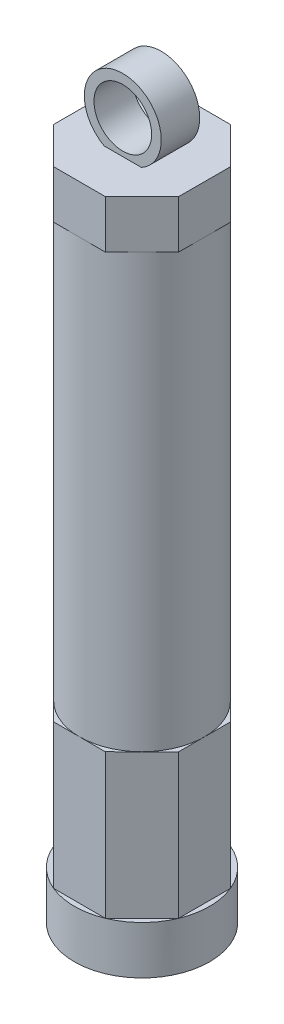
SolidWorks part; units mm, degrees
ref_plane "Front Plane" through (0, 0, 0) normal (0, 0, 1) x (1, 0, 0)
ref_plane "Top Plane" through (0, 0, 0) normal (0, 1, 0) x (1, 0, 0)
ref_plane "Right Plane" through (0, 0, 0) normal (1, 0, 0) x (0, 0, -1)
sketch "Sketch1" plane through (0, 0, 0) normal (0, 1, 0) x (1, 0, 0)
  circle A0 centre (0, 0) radius 6.5
  dimension "D1" = 13
extrude "Boss-Extrude1" add sketch "Sketch1" along normal blind 45
sketch "Sketch2" plane through (0, 45, 0) normal (0, 1, 0) x (1, 0, 0)
  line L0 (-6.5033, -2.6844) -> (-2.7004, -6.4967)
  line L1 (2.6844, -6.5033) -> (6.4967, -2.7004)
  line L2 (6.4967, -2.7004) -> (6.5033, 2.6844)
  line L3 (6.5033, 2.6844) -> (2.7004, 6.4967)
  line L4 (2.7004, 6.4967) -> (-2.6844, 6.5033)
  line L5 (-2.6844, 6.5033) -> (-6.4967, 2.7004)
  line L6 (-6.4967, 2.7004) -> (-6.5033, -2.6844)
  line L7 (-2.7004, -6.4967) -> (2.6844, -6.5033)
  line L8 (0, 0) -> (0, -6.5) construction
  line L9 (0, 0) -> (-1.6758, -4.0457) construction
  circle A0 centre (0, 0) radius 6.5 construction
  dimension "D1" = 13
  dimension "D2" = 22.5
extrude "Boss-Extrude2" add sketch "Sketch2" along normal blind 5
sketch "Sketch3" plane through (0, 0, 0) normal (0, -1, 0) x (1, 0, 0)
  line L1 (-2.7004, 6.4967) -> (-6.5033, 2.6844)
  line L2 (-6.5033, 2.6844) -> (-6.4967, -2.7004)
  line L3 (-6.4967, -2.7004) -> (-2.6844, -6.5033)
  line L4 (-2.6844, -6.5033) -> (2.7004, -6.4967)
  line L5 (2.7004, -6.4967) -> (6.5033, -2.6844)
  line L6 (6.5033, -2.6844) -> (6.4967, 2.7004)
  line L7 (6.4967, 2.7004) -> (2.6844, 6.5033)
  line L8 (2.6844, 6.5033) -> (-2.7004, 6.4967)
  circle A0 centre (0, 0) radius 6.5 construction
extrude "Boss-Extrude3" add sketch "Sketch3" along normal blind 15
sketch "Sketch4" plane through (0, -15, 0) normal (0, -1, 0) x (1, 0, 0)
  circle A0 centre (0, 0) radius 7.0355
extrude "Boss-Extrude4" add sketch "Sketch4" along normal blind 5
sketch "Sketch5" plane through (0, 0, 0) normal (0, 0, 1) x (1, 0, 0)
  line L0 (-2.7004, 50) -> (2.6844, 50) construction
  line L1 (1.9365, 50) -> (-1.9365, 50)
  circle A0 centre (0, 53.5) radius 3
  arc A1 (1.9365, 50) -> (-1.9365, 50) centre (0, 53.5) ccw
  dimension "D1" = 6
  dimension "D2" = 8
  dimension "D3" = 3.5
extrude "Boss-Extrude5" add sketch "Sketch5" along normal mid plane 4
